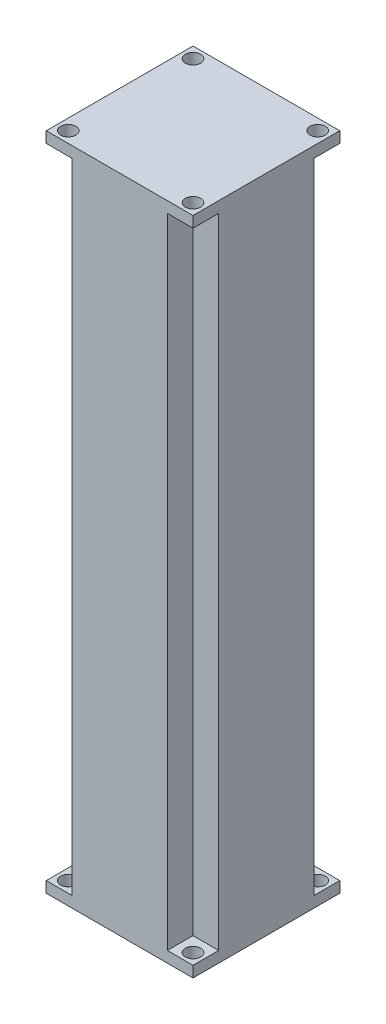
SolidWorks part; units mm, degrees
ref_plane "Front Plane" through (0, 0, 0) normal (0, 0, 1) x (1, 0, 0)
ref_plane "Top Plane" through (0, 0, 0) normal (0, 1, 0) x (1, 0, 0)
ref_plane "Right Plane" through (0, 0, 0) normal (1, 0, 0) x (0, 0, -1)
sketch "Sketch1" plane through (0, 0, 0) normal (0, 1, 0) x (1, 0, 0)
  line L1 (25.4, -25.4) -> (-25.4, -25.4)
  line L2 (25.4, -25.4) -> (25.4, 25.4)
  line L3 (25.4, 25.4) -> (-25.4, 25.4)
  line L4 (-25.4, -25.4) -> (-25.4, 25.4)
  line L5 (25.4, -25.4) -> (-25.4, 25.4) construction
  line L6 (25.4, 25.4) -> (-25.4, -25.4) construction
  point P0 (0, 0)
  dimension "D1" = 50.8
  dimension "D2" = 50.8
extrude "Boss-Extrude1" add sketch "Sketch1" along normal blind 228.6 contours L4 L3 L2 L1
sketch "Sketch2" plane through (0, 0, 25.4) normal (0, 0, 1) x (1, 0, 0)
  line L0 (25.4, 228.6) -> (25.4, 0) construction
  line L1 (25.4, 3.81) -> (16.51, 3.81)
  line L2 (25.4, 3.81) -> (25.4, 224.79)
  line L3 (25.4, 224.79) -> (16.51, 224.79)
  line L4 (16.51, 3.81) -> (16.51, 224.79)
  line L5 (25.4, 228.6) -> (-25.4, 228.6) construction
  line L6 (25.4, 0) -> (-25.4, 0) construction
  line L7 (0, 228.6) -> (0, 0) construction
  dimension "D1" = 3.81
  dimension "D2" = 3.81
  dimension "D3" = 8.89
extrude "Cut-Extrude1" cut sketch "Sketch2" against normal blind 8.89
sketch "Sketch3" plane through (0, 3.81, 0) normal (0, 1, 0) x (1, 0, 0)
  line L1 (25.4, -16.51) -> (25.4, -25.4) construction
  line L2 (16.51, -25.4) -> (25.4, -25.4) construction
  point P0 (21.59, -21.59)
  dimension "D1" = 3.81
  dimension "D2" = 3.81
hole_wizard "#4 (0.209) Diameter Hole1" positions "Sketch3" profile "Sketch4" hole size "#4" standard "ANSI Inch"
sketch "Sketch4" plane through (21.59, 3.81, 21.59) normal (1, 0, 0) x (0, 0, 1)
  line L0 (0, 0) -> (0, 3.81)
  line L1 (0, 3.81) -> (2.6543, 3.81)
  line L2 (2.6543, 3.81) -> (2.6543, 0)
  line L5 (2.6543, 0) -> (0, 0)
  line L11 (0, -6.35) -> (0, 107.95) construction
  dimension "Thru Hole Dia." = 5.3086
  dimension "Thru Hole Depth" = 3.81
sketch "Sketch5" plane through (0, 224.79, 0) normal (0, -1, 0) x (-1, 0, 0)
  point P0 (-21.59, -21.59)
hole_wizard "#4 (0.209) Diameter Hole2" positions "Sketch5" profile "Sketch6" hole size "#4" standard "ANSI Inch" end condition through all
sketch "Sketch6" plane through (21.59, 224.79, 21.59) normal (1, 0, 0) x (0, 0, -1)
  line L0 (0, 0) -> (0, 3.81)
  line L1 (0, 3.81) -> (2.6543, 3.81)
  line L2 (2.6543, 3.81) -> (2.6543, 0)
  line L5 (2.6543, 0) -> (0, 0)
  line L11 (0, -6.35) -> (0, 107.95) construction
  dimension "Thru Hole Dia." = 5.3086
  dimension "Thru Hole Depth" = 3.81
mirror "Mirror1" about plane through (0, 0, 0) normal (1, 0, 0) of "#4 (0.209) Diameter Hole2", "#4 (0.209) Diameter Hole1", "Cut-Extrude1" second plane through (0, 0, 0) second plane normal (0, 0, 1)
